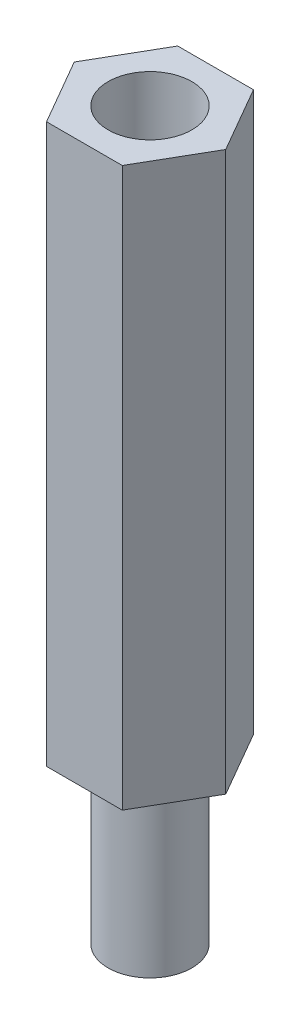
SolidWorks part; units mm, degrees
material "黄铜"
ref_plane "前视基准面" through (0, 0, 0) normal (0, 0, 1) x (1, 0, 0)
ref_plane "上视基准面" through (0, 0, 0) normal (0, 1, 0) x (1, 0, 0)
ref_plane "右视基准面" through (0, 0, 0) normal (1, 0, 0) x (0, 0, -1)
sketch "草图1" plane through (0, 0, 0) normal (0, 1, 0) x (1, 0, 0)
  line L1 (2.7135, 0) -> (1.3568, 2.35)
  line L2 (1.3568, 2.35) -> (-1.3568, 2.35)
  line L3 (-1.3568, 2.35) -> (-2.7135, 0)
  line L4 (-2.7135, 0) -> (-1.3568, -2.35)
  line L5 (-1.3568, -2.35) -> (1.3568, -2.35)
  line L6 (1.3568, -2.35) -> (2.7135, 0)
  circle A0 centre (0, 0) radius 1.5
  circle A1 centre (0, 0) radius 2.35 construction
  dimension "D1" = 3
  dimension "D2" = 4.7
extrude "凸台-拉伸1" add sketch "草图1" along normal blind 20
sketch "草图2" plane through (0, 0, 0) normal (0, -1, 0) x (-1, 0, 0)
  circle A0 centre (0, 0) radius 1.5
extrude "凸台-拉伸2" add sketch "草图2" along normal blind 6 separate body
